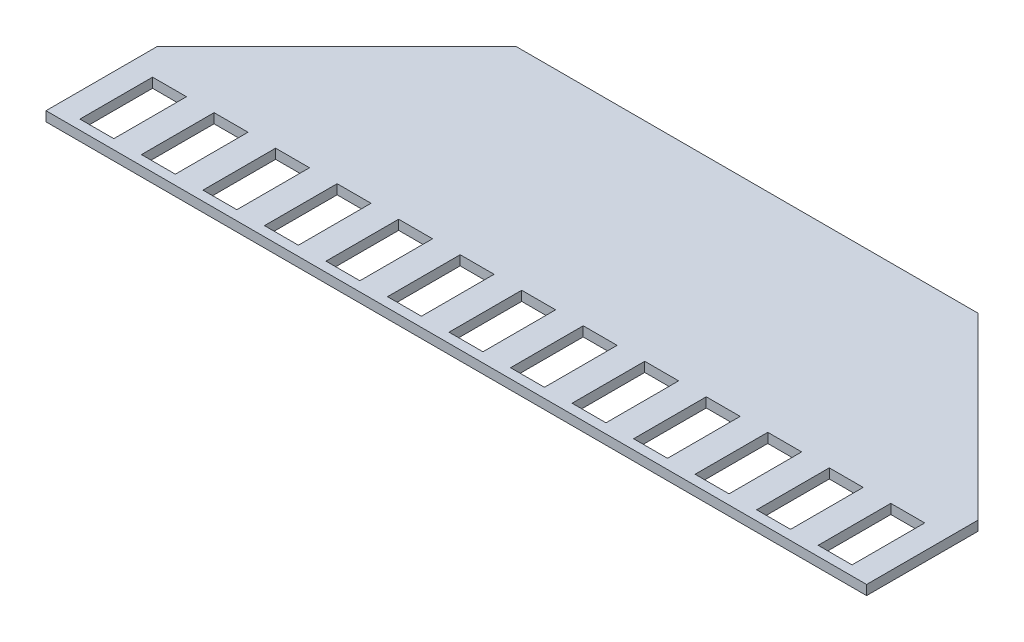
SolidWorks part; units mm, degrees
ref_plane "정면" through (0, 0, 0) normal (0, 0, 1) x (1, 0, 0)
ref_plane "윗면" through (0, 0, 0) normal (0, 1, 0) x (1, 0, 0)
ref_plane "우측면" through (0, 0, 0) normal (1, 0, 0) x (0, 0, -1)
sketch "스케치1" plane through (0, 0, 0) normal (0, -1, 0) x (1, 0, 0)
  line L0 (12.03, -3) -> (12.03, -4.5) construction
  line L1 (12.03, -4.5) -> (12.73, -4.5) construction
  line L2 (12.73, -4.5) -> (12.73, -3) construction
  line L3 (12.73, -3) -> (12.03, -3) construction
  line L4 (13.3, -3) -> (13.3, -4.5) construction
  line L5 (13.3, -4.5) -> (14, -4.5) construction
  line L6 (14, -4.5) -> (14, -3) construction
  line L7 (14, -3) -> (13.3, -3) construction
  line L8 (14.57, -3) -> (14.57, -4.5) construction
  line L9 (14.57, -4.5) -> (15.27, -4.5) construction
  line L10 (15.27, -4.5) -> (15.27, -3) construction
  line L11 (15.27, -3) -> (14.57, -3) construction
  line L12 (15.84, -3) -> (15.84, -4.5) construction
  line L13 (15.84, -4.5) -> (16.54, -4.5) construction
  line L14 (16.54, -4.5) -> (16.54, -3) construction
  line L15 (16.54, -3) -> (15.84, -3) construction
  line L16 (17.11, -3) -> (17.11, -4.5) construction
  line L17 (17.11, -4.5) -> (17.81, -4.5) construction
  line L18 (17.81, -4.5) -> (17.81, -3) construction
  line L19 (17.81, -3) -> (17.11, -3) construction
  line L20 (18.38, -3) -> (18.38, -4.5) construction
  line L21 (18.38, -4.5) -> (19.08, -4.5) construction
  line L22 (19.08, -4.5) -> (19.08, -3) construction
  line L23 (19.08, -3) -> (18.38, -3) construction
  line L24 (19.65, -3) -> (19.65, -4.5) construction
  line L25 (19.65, -4.5) -> (20.35, -4.5) construction
  line L26 (20.35, -4.5) -> (20.35, -3) construction
  line L27 (20.35, -3) -> (19.65, -3) construction
  line L28 (20.92, -3) -> (20.92, -4.5) construction
  line L29 (20.92, -4.5) -> (21.62, -4.5) construction
  line L30 (21.62, -4.5) -> (21.62, -3) construction
  line L31 (21.62, -3) -> (20.92, -3) construction
  line L32 (22.19, -3) -> (22.19, -4.5) construction
  line L33 (22.19, -4.5) -> (22.89, -4.5) construction
  line L34 (22.89, -4.5) -> (22.89, -3) construction
  line L35 (22.89, -3) -> (22.19, -3) construction
  line L36 (23.46, -3) -> (23.46, -4.5) construction
  line L37 (23.46, -4.5) -> (24.16, -4.5) construction
  line L38 (24.16, -4.5) -> (24.16, -3) construction
  line L39 (24.16, -3) -> (23.46, -3) construction
  line L40 (24.73, -3) -> (24.73, -4.5) construction
  line L41 (24.73, -4.5) -> (25.43, -4.5) construction
  line L42 (25.43, -4.5) -> (25.43, -3) construction
  line L43 (25.43, -3) -> (24.73, -3) construction
  line L44 (26, -3) -> (26, -4.5) construction
  line L45 (26, -4.5) -> (26.7, -4.5) construction
  line L46 (26.7, -4.5) -> (26.7, -3) construction
  line L47 (26.7, -3) -> (26, -3) construction
  line L48 (27.27, -3) -> (27.27, -4.5) construction
  line L49 (27.27, -4.5) -> (27.97, -4.5) construction
  line L50 (27.97, -4.5) -> (27.97, -3) construction
  line L51 (27.97, -3) -> (27.27, -3) construction
  line L52 (12.03, -3) -> (12.03, -4.5)
  line L53 (12.03, -4.5) -> (12.73, -4.5)
  line L54 (12.73, -4.5) -> (12.73, -3)
  line L55 (12.73, -3) -> (12.03, -3)
  line L56 (13.3, -3) -> (13.3, -4.5)
  line L57 (13.3, -4.5) -> (14, -4.5)
  line L58 (14, -4.5) -> (14, -3)
  line L59 (14, -3) -> (13.3, -3)
  line L60 (14.57, -3) -> (14.57, -4.5)
  line L61 (14.57, -4.5) -> (15.27, -4.5)
  line L62 (15.27, -4.5) -> (15.27, -3)
  line L63 (15.27, -3) -> (14.57, -3)
  line L64 (15.84, -3) -> (15.84, -4.5)
  line L65 (15.84, -4.5) -> (16.54, -4.5)
  line L66 (16.54, -4.5) -> (16.54, -3)
  line L67 (16.54, -3) -> (15.84, -3)
  line L68 (17.11, -3) -> (17.11, -4.5)
  line L69 (17.11, -4.5) -> (17.81, -4.5)
  line L70 (17.81, -4.5) -> (17.81, -3)
  line L71 (17.81, -3) -> (17.11, -3)
  line L72 (18.38, -3) -> (18.38, -4.5)
  line L73 (18.38, -4.5) -> (19.08, -4.5)
  line L74 (19.08, -4.5) -> (19.08, -3)
  line L75 (19.08, -3) -> (18.38, -3)
  line L76 (19.65, -3) -> (19.65, -4.5)
  line L77 (19.65, -4.5) -> (20.35, -4.5)
  line L78 (20.35, -4.5) -> (20.35, -3)
  line L79 (20.35, -3) -> (19.65, -3)
  line L80 (20.92, -3) -> (20.92, -4.5)
  line L81 (20.92, -4.5) -> (21.62, -4.5)
  line L82 (21.62, -4.5) -> (21.62, -3)
  line L83 (21.62, -3) -> (20.92, -3)
  line L84 (22.19, -3) -> (22.19, -4.5)
  line L85 (22.19, -4.5) -> (22.89, -4.5)
  line L86 (22.89, -4.5) -> (22.89, -3)
  line L87 (22.89, -3) -> (22.19, -3)
  line L88 (23.46, -3) -> (23.46, -4.5)
  line L89 (23.46, -4.5) -> (24.16, -4.5)
  line L90 (24.16, -4.5) -> (24.16, -3)
  line L91 (24.16, -3) -> (23.46, -3)
  line L92 (24.73, -3) -> (24.73, -4.5)
  line L93 (24.73, -4.5) -> (25.43, -4.5)
  line L94 (25.43, -4.5) -> (25.43, -3)
  line L95 (25.43, -3) -> (24.73, -3)
  line L96 (26, -3) -> (26, -4.5)
  line L97 (26, -4.5) -> (26.7, -4.5)
  line L98 (26.7, -4.5) -> (26.7, -3)
  line L99 (26.7, -3) -> (26, -3)
  line L100 (27.27, -3) -> (27.27, -4.5)
  line L101 (27.27, -4.5) -> (27.97, -4.5)
  line L102 (27.97, -4.5) -> (27.97, -3)
  line L103 (27.97, -3) -> (27.27, -3)
  line L104 (28.47, -5.1) -> (24.77, -8.8)
  line L105 (28.47, -2.8) -> (11.53, -2.8)
  line L106 (28.47, -2.8) -> (28.47, -5.1)
  line L107 (11.53, -5.1) -> (15.23, -8.8)
  line L108 (11.53, -2.8) -> (11.53, -5.1)
  line L109 (15.23, -8.8) -> (24.77, -8.8)
  dimension "D1" = 0.2
  dimension "D2" = 0.5
  dimension "D3" = 0.5
  dimension "D4" = 45
  dimension "D5" = 45
  dimension "D6" = 6
  dimension "D7" = 2.3
extrude "보스-돌출1" add sketch "스케치1" along normal blind 0.2
equation "\"D3@스케치1\"=\"D2@스케치1\""
equation "\"D5@스케치1\"=\"D4@스케치1\""
